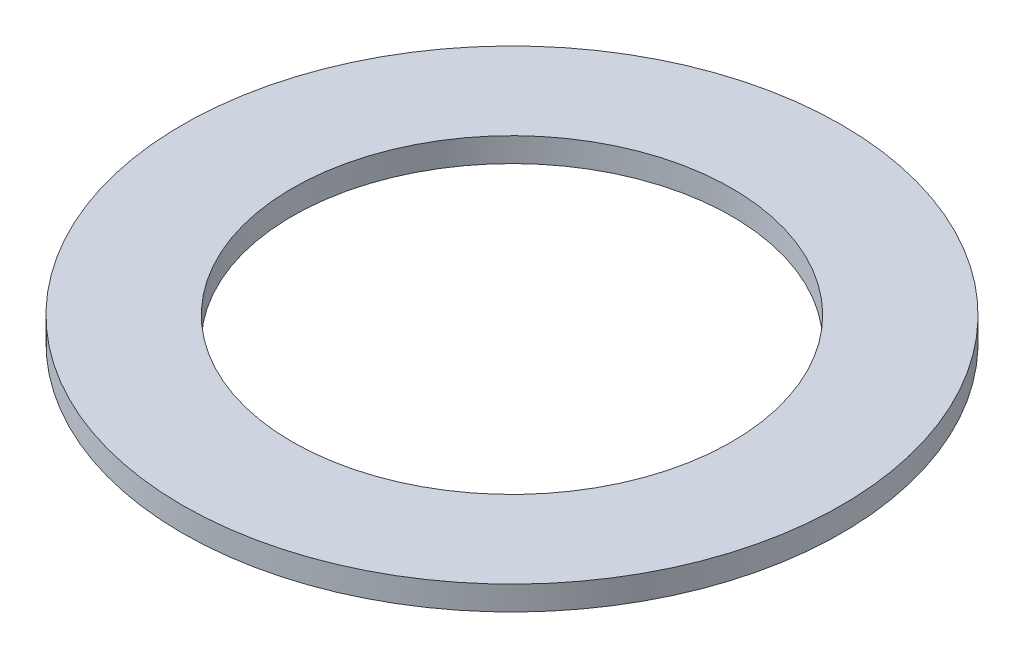
SolidWorks part; units mm, degrees
ref_plane "Front Plane" through (0, 0, 0) normal (0, 0, 1) x (1, 0, 0)
ref_plane "Top Plane" through (0, 0, 0) normal (0, 1, 0) x (1, 0, 0)
ref_plane "Right Plane" through (0, 0, 0) normal (1, 0, 0) x (0, 0, -1)
sketch "Sketch1" plane through (0, 0, 0) normal (0, 1, 0) x (1, 0, 0)
  circle A0 centre (0, 0) radius 75
  circle A1 centre (0, 0) radius 50
  dimension "D1" = 100
  dimension "D2" = 150
extrude "Boss-Extrude1" add sketch "Sketch1" along normal blind 5.5
